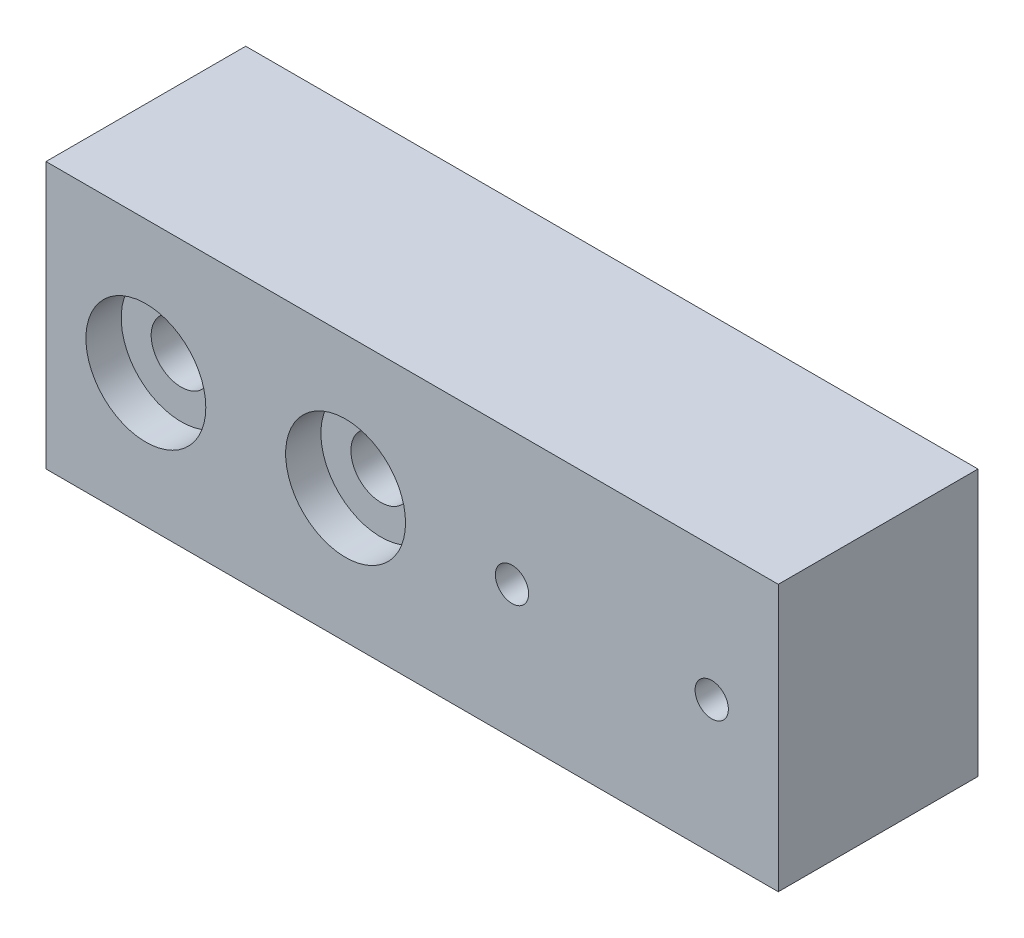
SolidWorks part; units mm, degrees
material "6061-T6 (SS)"
ref_plane "Front Plane" through (0, 0, 0) normal (0, 0, 1) x (1, 0, 0)
ref_plane "Top Plane" through (0, 0, 0) normal (0, 1, 0) x (1, 0, 0)
ref_plane "Right Plane" through (0, 0, 0) normal (1, 0, 0) x (0, 0, -1)
sketch "Sketch1" plane through (0, 0, 0) normal (0, 0, 1) x (1, 0, 0)
  line L1 (-55, -20) -> (55, -20)
  line L2 (-55, -20) -> (-55, 20)
  line L3 (-55, 20) -> (55, 20)
  line L4 (55, -20) -> (55, 20)
  dimension "D1" = 55
  dimension "D2" = 20
  dimension "D3" = 55
  dimension "D4" = 20
extrude "BRACKET" add sketch "Sketch1" along normal blind 30
ref_plane "OUTER_REF" through (0, 0, 30) normal (0, 0, 1) x (1, 0, 0)
sketch "Sketch6" plane through (0, 0, 30) normal (0, 0, 1) x (1, 0, 0)
  line L0 (-55, 20) -> (-55, -20) construction
  line L1 (55, 20) -> (-55, 20) construction
  point P0 (-40, 0)
  point P1 (-10, 0)
  point P2 (15, 0)
  point P3 (45, 0)
  dimension "D1" = 15
  dimension "D2" = 20
  dimension "D3" = 20
  dimension "D4" = 20
  dimension "D5" = 20
  dimension "D6" = 30
  dimension "D7" = 25
  dimension "D8" = 30
hole_wizard "CBORE for M8 Hex Head Bolt1" positions "Sketch6" profile "Sketch8" counterbore size "M8" standard "ISO"
sketch "Sketch8" plane through (-40, 0, 30) normal (1, 0, 0) x (0, -1, 0)
  line L0 (0, 0) -> (0, 30)
  line L1 (0, 30) -> (4.5, 30)
  line L3 (4.5, 30) -> (4.5, 5.3)
  line L4 (4.5, 5.3) -> (9.0055, 5.3)
  line L5 (9.0055, 5.3) -> (9.0055, 0)
  line L7 (9.0055, 0) -> (0, 0)
  line L11 (0, -6.35) -> (0, 107.95) construction
  dimension "Thru Hole Dia." = 9
  dimension "Thru Hole Depth" = 30
  dimension "C'Bore Dia." = 18.011
  dimension "C'Bore Depth" = 5.3
sketch "Sketch9" plane through (0, 0, 30) normal (0, 0, 1) x (1, 0, 0)
  line L0 (55, -20) -> (55, 20) construction
  line L1 (55, 20) -> (-55, 20) construction
  point P0 (15, 0)
  point P1 (45, 0)
  dimension "D1" = 10
  dimension "D2" = 20
  dimension "D3" = 20
  dimension "D4" = 30
hole_wizard "M6 Tapped Hole1" positions "Sketch9" profile "Sketch11" tap size "M6" standard "ISO"
sketch "Sketch11" plane through (15, 0, 30) normal (1, 0, 0) x (0, -1, 0)
  line L0 (0, 0) -> (0, 11.5022)
  line L1 (0, 11.5022) -> (2.5, 10)
  line L2 (2.5, 10) -> (2.5, 0)
  line L5 (2.5, 0) -> (0, 0)
  line L10 (0, 11.5022) -> (-2.5, 10) construction
  line L11 (0, -6.35) -> (0, 107.95) construction
  dimension "Tap Drill Dia." = 5
  dimension "Tap Drill Depth" = 10
  dimension "Drill Angle" = 118
cosmetic thread "Hole Thread1" parameters "D1"=1, "D2"=6
cosmetic thread "Hole Thread2" parameters "D1"=1, "D2"=6
ref_plane "BRK_BACK" through (0, 0, 30) normal (0, 0, 1) x (1, 0, 0)
